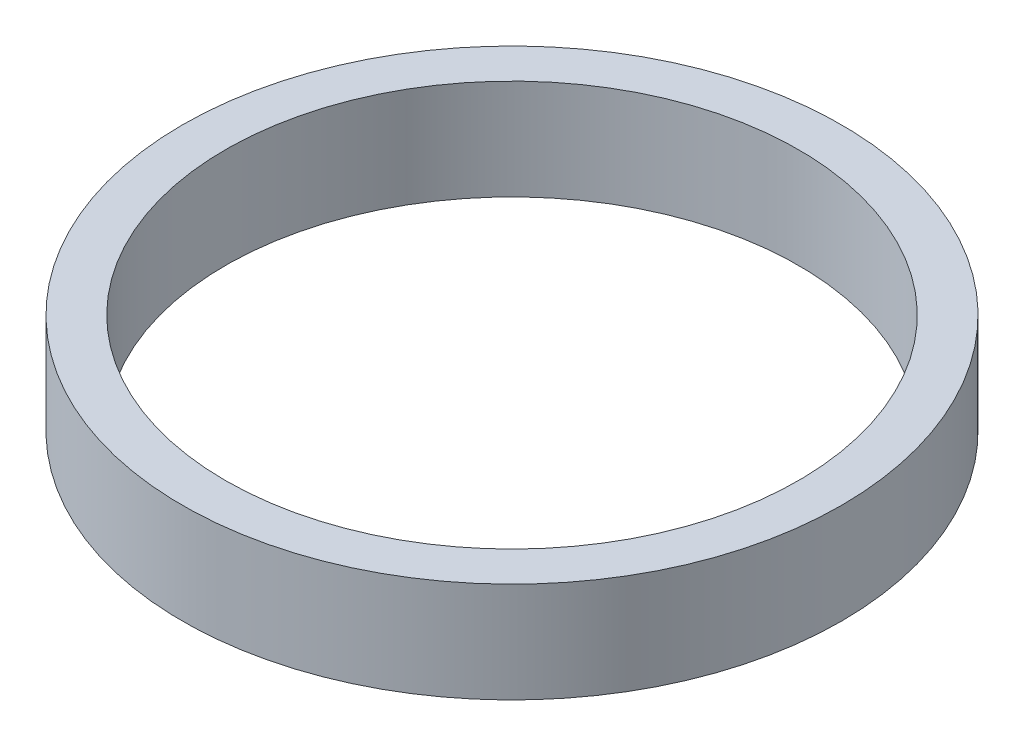
SolidWorks part; units mm, degrees
material "PVC 0.007 Plasticized"
ref_plane "Front Plane" through (0, 0, 0) normal (0, 0, 1) x (1, 0, 0)
ref_plane "Top Plane" through (0, 0, 0) normal (0, 1, 0) x (1, 0, 0)
ref_plane "Right Plane" through (0, 0, 0) normal (1, 0, 0) x (0, 0, -1)
sketch "Sketch1" plane through (0, 0, 0) normal (0, 1, 0) x (1, 0, 0)
  circle A0 centre (0, 0) radius 10
  dimension "D1" = 20
extrude "Extrude-Thin1" add sketch "Sketch1" along normal blind 3.5 thin
